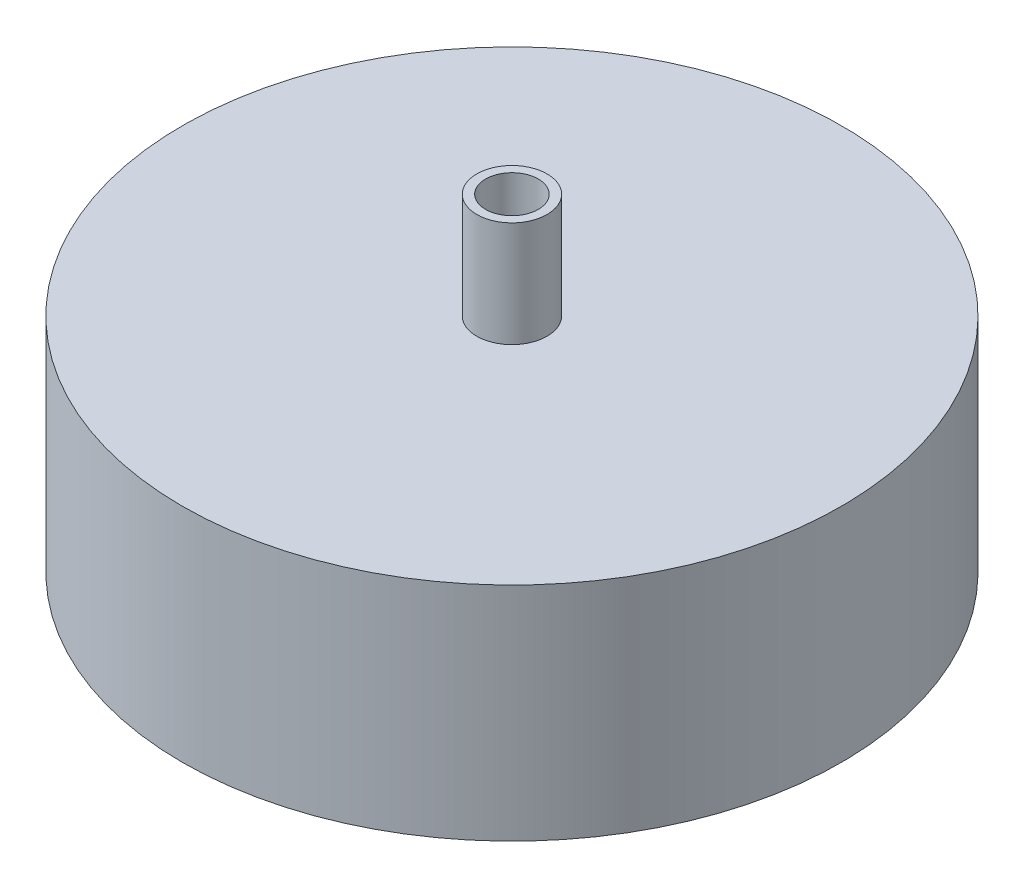
SolidWorks part; units mm, degrees
ref_plane "前视基准面" through (0, 0, 0) normal (0, 0, 1) x (1, 0, 0)
ref_plane "上视基准面" through (0, 0, 0) normal (0, 1, 0) x (1, 0, 0)
ref_plane "右视基准面" through (0, 0, 0) normal (1, 0, 0) x (0, 0, -1)
other "Configuration Table"
sketch "草图1" plane through (0, 0, 0) normal (0, 1, 0) x (1, 0, 0)
  circle A0 centre (0, 0) radius 37.5
  dimension "D1" = 75
extrude "凸台-拉伸1" add sketch "草图1" along normal blind 25.24
sketch "草图2" plane through (0, 25.24, 0) normal (0, 1, 0) x (1, 0, 0)
  circle A0 centre (0, 0) radius 3
  circle A1 centre (0, 0) radius 4
  dimension "D1" = 6
  dimension "D2" = 8
extrude "凸台-拉伸2" add sketch "草图2" along normal blind 12
sketch "草图3" plane through (0, 25.24, 0) normal (0, 1, 0) x (1, 0, 0)
  circle A0 centre (0, 0) radius 3 construction
  circle A1 centre (0, 0) radius 3
extrude "切除-拉伸1" cut sketch "草图3" against normal up to next
